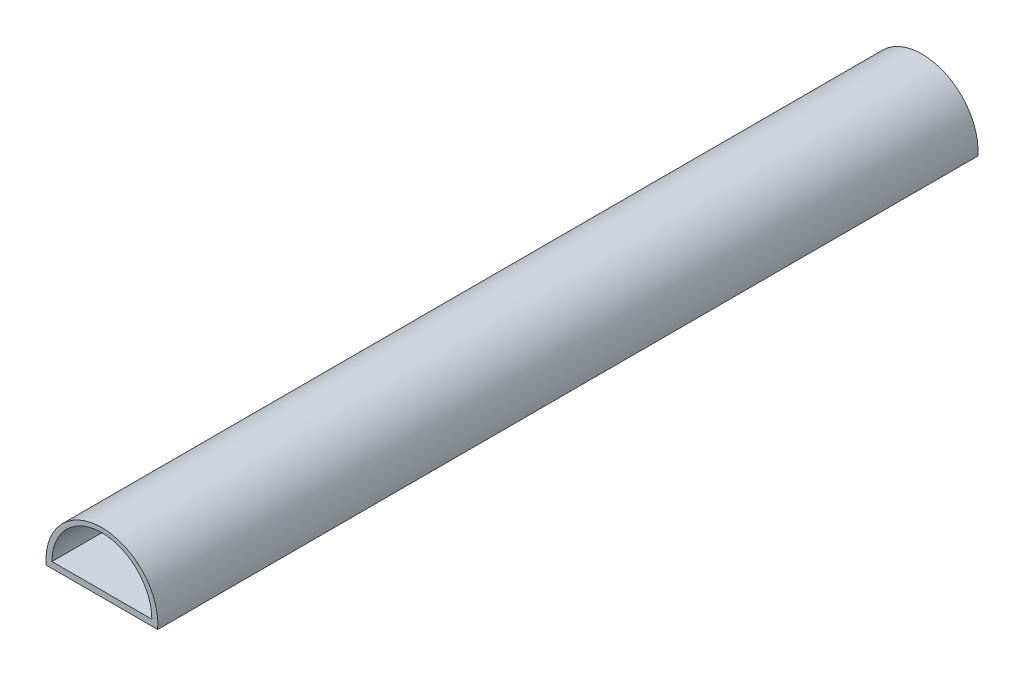
SolidWorks part; units mm, degrees
material "PVC 0.007 Plasticized"
ref_plane "Front Plane" through (0, 0, 0) normal (0, 0, 1) x (1, 0, 0)
ref_plane "Top Plane" through (0, 0, 0) normal (0, 1, 0) x (1, 0, 0)
ref_plane "Right Plane" through (0, 0, 0) normal (1, 0, 0) x (0, 0, -1)
sketch "Sketch1" plane through (0, 0, 0) normal (0, 0, 1) x (1, 0, 0)
  line L0 (-23.1114, -10.0484) -> (6.2574, -10.0484)
  line L2 (-8.427, -8.4609) -> (-21.5715, -8.4609)
  line L3 (-8.427, -8.4609) -> (4.7175, -8.4609)
  arc A0 (-23.1114, -10.0484) -> (6.2574, -10.0484) centre (-8.427, -8.8769) cw
  arc A1 (-21.5715, -8.4609) -> (4.7175, -8.4609) centre (-8.427, -8.4609) cw
extrude "Boss-Extrude2" add sketch "Sketch1" along normal blind 215.9
